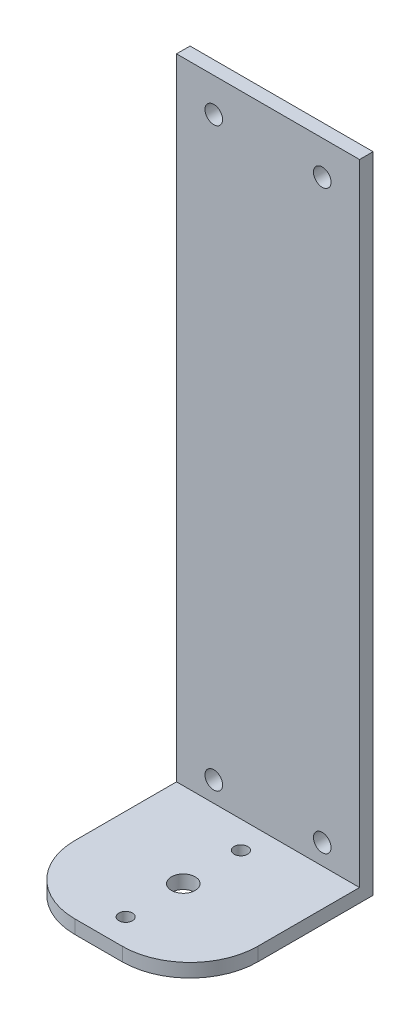
SolidWorks part; units mm, degrees
ref_plane "Front Plane" through (0, 0, 0) normal (1, 0, 0) x (0, 1, 0)
ref_plane "Top Plane" through (0, 0, 0) normal (0, 0, 1) x (0, 1, 0)
ref_plane "Right Plane" through (0, 0, 0) normal (0, 1, 0) x (-1, 0, 0)
sketch "Sketch1" plane through (0, 0, 0) normal (0, 0, 1) x (0, 1, 0)
  line L1 (-11.2105, 4.153) -> (15.7895, 4.153)
  line L2 (-11.2105, 4.153) -> (-11.2105, -22.847)
  line L3 (-11.2105, -22.847) -> (15.7895, -22.847)
  line L4 (15.7895, 4.153) -> (15.7895, -22.847)
  dimension "D1" = 27
  dimension "D2" = 27
extrude "Boss-Extrude1" add sketch "Sketch1" along normal blind 27
sketch "Sketch2" plane through (22.847, 0, 0) normal (1, 0, 0) x (0, 1, 0)
  line L1 (15.7895, 27) -> (-9.2105, 27)
  line L2 (15.7895, 27) -> (15.7895, 2)
  line L3 (15.7895, 2) -> (-9.2105, 2)
  line L4 (-9.2105, 27) -> (-9.2105, 2)
  dimension "D1" = 25
  dimension "D2" = 25
extrude "Cut-Extrude1" cut sketch "Sketch2" against normal up to next
sketch "Sketch3" plane through (0, -9.2105, 0) normal (0, 1, 0) x (-1, 0, 0)
  line L0 (-9.347, 27) -> (-9.347, 2) construction
  line L1 (4.153, 27) -> (-22.847, 27) construction
  line L2 (4.153, 2) -> (-22.847, 2) construction
  line L3 (-22.847, 14.5) -> (4.153, 14.5) construction
  line L4 (-22.847, 27) -> (-22.847, 2) construction
  line L5 (4.153, 2) -> (4.153, 27) construction
  circle A0 centre (-9.347, 14.5) radius 1.75
  circle A1 centre (-9.347, 23) radius 1
  circle A2 centre (-9.347, 6) radius 1
  dimension "D1" = 3.5
  dimension "D2" = 2
  dimension "D3" = 8.5
extrude "Cut-Extrude2" cut sketch "Sketch3" against normal up to next
sketch "Sketch4" plane through (0, 0, 2) normal (0, 0, 1) x (1, 0, 0)
  line L1 (-4.153, 15.7895) -> (22.847, 15.7895)
  line L2 (-4.153, 15.7895) -> (-4.153, 83.7895)
  line L3 (-4.153, 83.7895) -> (22.847, 83.7895)
  line L4 (22.847, 15.7895) -> (22.847, 83.7895)
  dimension "D1" = 68
  dimension "D2" = 27
extrude "Boss-Extrude2" add sketch "Sketch4" against normal blind 2
sketch "Sketch5" plane through (0, 0, 2) normal (0, 0, 1) x (1, 0, 0)
  line L0 (-4.153, -6.2105) -> (22.847, -6.2105) construction
  line L1 (-4.153, 83.7895) -> (-4.153, -9.2105) construction
  line L2 (22.847, -9.2105) -> (22.847, 83.7895) construction
  line L3 (9.347, -11.2105) -> (9.347, 83.7895) construction
  line L4 (-4.153, -11.2105) -> (22.847, -11.2105) construction
  line L5 (22.847, 83.7895) -> (-4.153, 83.7895) construction
  line L6 (-4.153, 78.7895) -> (22.847, 78.7895) construction
  circle A0 centre (1.347, -6.2105) radius 1.3
  circle A1 centre (1.347, 78.7895) radius 1.3
  circle A2 centre (17.347, -6.2105) radius 1.3
  circle A3 centre (17.347, 78.7895) radius 1.3
  dimension "D3" = 2.6
  dimension "D4" = 2.6
  dimension "D1" = 5
  dimension "D2" = 5
  dimension "D5" = 8
  dimension "D6" = 8
extrude "Cut-Extrude3" cut sketch "Sketch5" against normal up to next
fillet "Fillet1" radius 10 2 edges at (-4.153, -10.2105, 27) (22.847, -10.2105, 27)
